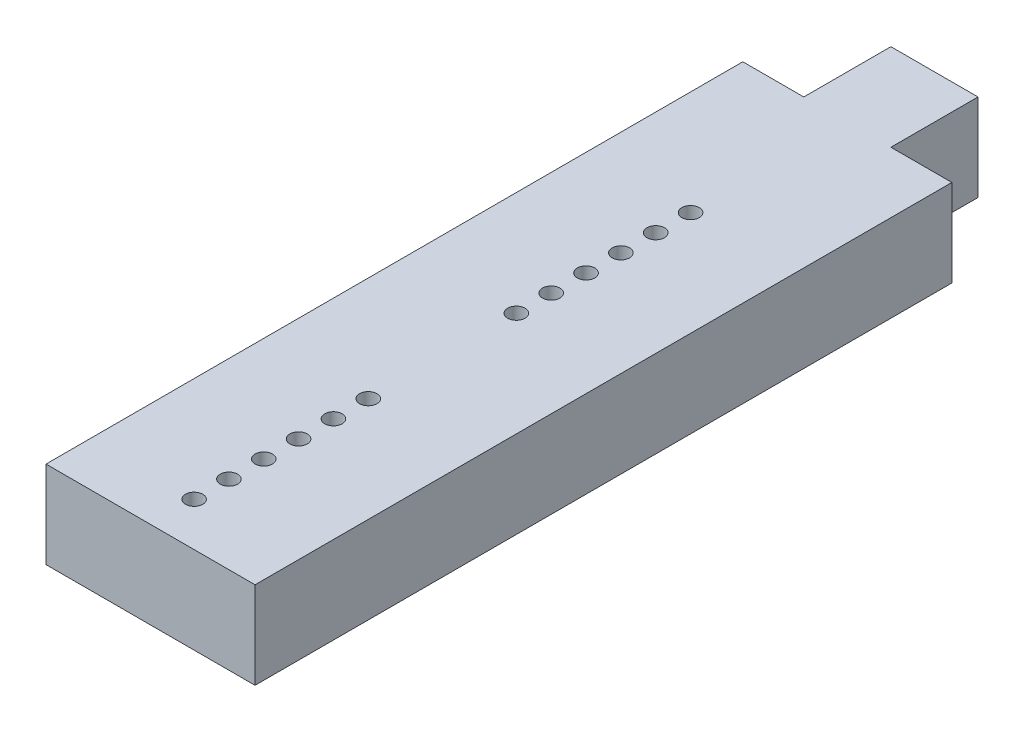
SolidWorks part; units mm, degrees
material "Acrylic (Medium-high impact)"
ref_plane "Front Plane" through (0, 0, 0) normal (0, 0, 1) x (1, 0, 0)
ref_plane "Top Plane" through (0, 0, 0) normal (0, 1, 0) x (1, 0, 0)
ref_plane "Right Plane" through (0, 0, 0) normal (1, 0, 0) x (0, 0, -1)
sketch "Sketch1" plane through (0, 0, 0) normal (0, 1, 0) x (1, 0, 0)
  line L0 (-2.5, 20) -> (-2.5, 25)
  line L1 (-6, 20) -> (-2.5, 20)
  line L2 (-6, 20) -> (-6, -20)
  line L3 (-6, -20) -> (6, -20)
  line L4 (6, 20) -> (6, -20)
  line L7 (-2.5, 25) -> (2.5, 25)
  line L8 (2.5, 25) -> (2.5, 20)
  line L9 (2.5, 20) -> (6, 20)
  circle A0 centre (0, 11) radius 0.5
  circle A1 centre (0, 9) radius 0.5
  circle A2 centre (0, 7) radius 0.5
  circle A3 centre (0, 5) radius 0.5
  circle A4 centre (0, 3) radius 0.5
  circle A5 centre (0, 1) radius 0.5
  circle A6 centre (0, -7.5) radius 0.5
  circle A7 centre (0, -9.5) radius 0.5
  circle A8 centre (0, -11.5) radius 0.5
  circle A9 centre (0, -13.5) radius 0.5
  circle A10 centre (0, -15.5) radius 0.5
  circle A11 centre (0, -17.5) radius 0.5
  point P0 (0, 0)
  point P8 (0, 25)
  point P11 (0, -20)
  point P13 (-6, 0)
  dimension "D5" = 1
  dimension "D8" = 2
  dimension "D9" = 1
  dimension "D1" = 12
  dimension "D2" = 40
  dimension "D3" = 5
  dimension "D4" = 5
  dimension "D6" = 9
  dimension "D10" = 8.5
  dimension "D12" = 2
  dimension "D7" = 6
  dimension "D11" = 6
extrude "Boss-Extrude1" add sketch "Sketch1" along normal blind 5
